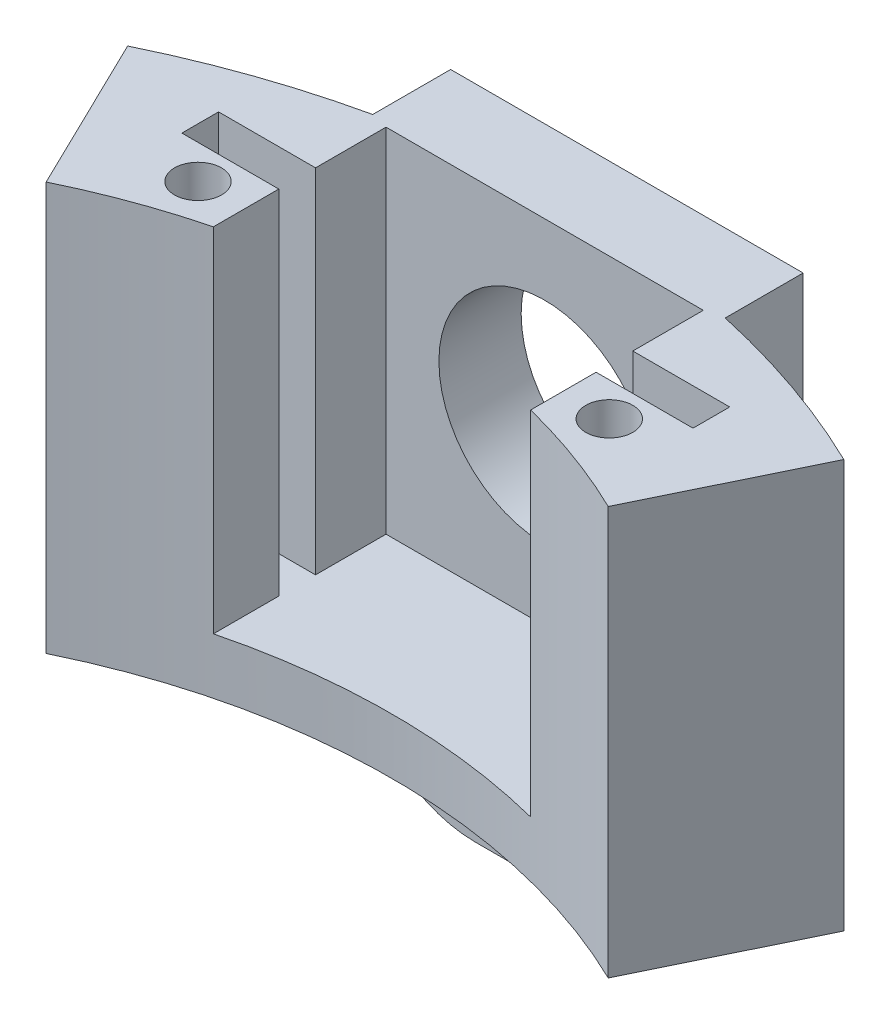
SolidWorks part; units mm, degrees
material "ABS"
ref_plane "Front Plane" through (0, 0, 0) normal (0, 0, 1) x (1, 0, 0)
ref_plane "Top Plane" through (0, 0, 0) normal (0, 1, 0) x (1, 0, 0)
ref_plane "Right Plane" through (0, 0, 0) normal (1, 0, 0) x (0, 0, -1)
sketch "Sketch1" plane through (0, 0, 0) normal (0, 1, 0) x (1, 0, 0)
  line L0 (0, 0) -> (6.5582, -13.4904)
  line L1 (60.9497, 0) -> (54.3915, -13.4904)
  arc A0 (0, 0) -> (60.9497, 0) centre (30.4748, -62.6878) cw
  arc A1 (6.5582, -13.4904) -> (54.3915, -13.4904) centre (30.4748, -62.6878) cw
  dimension "D1" = 15
extrude "Boss-Extrude1" add sketch "Sketch1" along normal blind 34.75
sketch "Sketch2" plane through (0, 34.75, 0) normal (0, 1, 0) x (1, 0, 0)
  arc A0 (60.9497, 0) -> (0, 0) centre (30.4748, -62.6878) ccw construction
  circle A2 centre (12.9748, -6.985) radius 2
  circle A3 centre (47.9748, -6.985) radius 2
  point P3 (30.4748, 7.015)
  dimension "D1" = 4
  dimension "D2" = 17.5
  dimension "D3" = 17.5
  dimension "D4" = 14
  dimension "D5" = 14
extrude "Cut-Extrude1" cut sketch "Sketch2" against normal through all
sketch "Sketch3" plane through (0, 34.75, 0) normal (0, 1, 0) x (1, 0, 0)
  line L2 (15.4748, 12.015) -> (45.4748, 12.015)
  line L3 (45.4748, 12.015) -> (45.4748, 4.1184)
  line L4 (45.4748, 4.1184) -> (15.4748, 4.1184)
  line L5 (15.4748, 12.015) -> (15.4748, 4.1184)
  point P15 (30.4748, 4.1184)
extrude "Boss-Extrude2" add sketch "Sketch3" against normal blind 48
sketch "Sketch4" plane through (0, 0, -4.1184) normal (0, 0, 1) x (1, 0, 0)
  line L0 (15.4748, -13.25) -> (15.4748, 0) construction
  line L1 (45.4748, 0) -> (15.4748, 0)
  line L2 (45.4748, 0) -> (45.4748, -6)
  line L3 (45.4748, -6) -> (15.4748, -6)
  line L4 (15.4748, 0) -> (15.4748, -6)
  dimension "D1" = 6
extrude "Cut-Extrude2" cut sketch "Sketch4" against normal blind 4
fillet "Fillet1" radius 10 2 edges at (15.4748, -13.25, -8.0667) (45.4748, -13.25, -8.0667)
sketch "Sketch5" plane through (0, 0, -12.015) normal (0, 0, -1) x (-1, 0, 0)
  line L0 (-45.4748, 34.75) -> (-15.4748, 34.75) construction
  circle A0 centre (-30.4748, 19.75) radius 9
  dimension "D1" = 18
  dimension "D2" = 15
extrude "Cut-Extrude3" cut sketch "Sketch5" against normal through all
sketch "Sketch7" plane through (0, 0, -12.015) normal (0, 0, -1) x (-1, 0, 0)
  line L0 (-21.5361, 1.4539) -> (-26.1998, 0)
  line L1 (-34.426, 3.6737) -> (-38.9602, 5.6642)
  arc A0 (-26.1998, 0) -> (-21.5361, 1.4539) centre (-24.0106, 1.1845) cw
  arc A1 (-34.426, 3.6737) -> (-38.9602, 5.6642) centre (-36.8827, 4.237) cw
extrude "Boss-Extrude3" add sketch "Sketch7" along normal blind 1
sketch "Sketch8" plane through (0, 0, -13.015) normal (0, 0, -1) x (-1, 0, 0)
  line L0 (-23.0227, 0.9904) -> (-25.0369, 0.3625)
  line L1 (-26.1998, 0) -> (-21.5361, 1.4539) construction
  line L2 (-26.1998, 0) -> (-21.5361, 1.4539) construction
  line L3 (-35.7508, 4.2552) -> (-37.8939, 5.1961)
  line L4 (-34.426, 3.6737) -> (-38.9602, 5.6642) construction
  line L5 (-34.426, 3.6737) -> (-38.9602, 5.6642) construction
  arc A0 (-23.0227, 0.9904) -> (-25.0369, 0.3625) centre (-24.1419, 1.0361) ccw
  arc A1 (-35.7508, 4.2552) -> (-37.8939, 5.1961) centre (-36.9613, 4.4092) cw
extrude "Cut-Extrude4" cut sketch "Sketch8" against normal blind 0.5
sketch "Sketch9" plane through (0, 34.75, 0) normal (0, 1, 0) x (1, 0, 0)
  line L0 (30.4748, -7.985) -> (30.4748, 5.015)
  line L1 (43.9748, 5.015) -> (16.9748, 5.015)
  line L2 (16.9748, 5.015) -> (16.9748, -15.6148)
  line L3 (16.9748, -15.6148) -> (43.9748, -15.6148)
  line L4 (30.4748, -15.6148) -> (30.4748, -7.985)
  line L5 (43.9748, 5.015) -> (43.9748, -15.6148)
  arc A0 (54.3915, -13.4904) -> (6.5582, -13.4904) centre (30.4748, -62.6878) ccw construction
  arc M12 (6.5582, -13.4904) -> (54.3915, -13.4904) centre (30.4748, -62.6878) cw
  dimension "D1" = 13.5
  dimension "D2" = 13
extrude "Cut-Extrude5" cut sketch "Sketch9" against normal blind 30 contours L5 L1 L0 M12 | L1 L2 L0 M12
sketch "Sketch11" plane through (0, 34.75, 0) normal (0, 1, 0) x (1, 0, 0)
  line L0 (16.9748, 5.015) -> (16.9748, -9.677) construction
  line L1 (16.9748, -0.985) -> (8.7248, -0.985)
  line L2 (16.9748, -0.985) -> (16.9748, -4.11)
  line L3 (16.9748, -4.11) -> (8.7248, -4.11)
  line L4 (8.7248, -0.985) -> (8.7248, -4.11)
  line L5 (30.4748, 12.015) -> (30.4748, 7.4364)
  line L6 (45.4748, 12.015) -> (15.4748, 12.015) construction
  line L7 (43.9748, 5.015) -> (16.9748, 5.015) construction
  line L8 (43.9748, -0.985) -> (52.2248, -0.985)
  line L9 (43.9748, -0.985) -> (43.9748, -4.11)
  line L10 (52.2248, -0.985) -> (52.2248, -4.11)
  line L11 (43.9748, -4.11) -> (52.2248, -4.11)
  circle M6 centre (47.9748, -6.985) radius 2
  circle M7 centre (12.9748, -6.985) radius 2
  line M8 (43.9748, 5.015) -> (43.9748, -9.677)
  line M18 (16.9748, -9.677) -> (16.9748, 5.015)
  dimension "D1" = 8.25
  dimension "D2" = 3.125
  dimension "D3" = 6
extrude "Cut-Extrude6" cut sketch "Sketch11" against normal blind 30 contours L11 L8 M8 M6 | L3 L1 M18 M7
